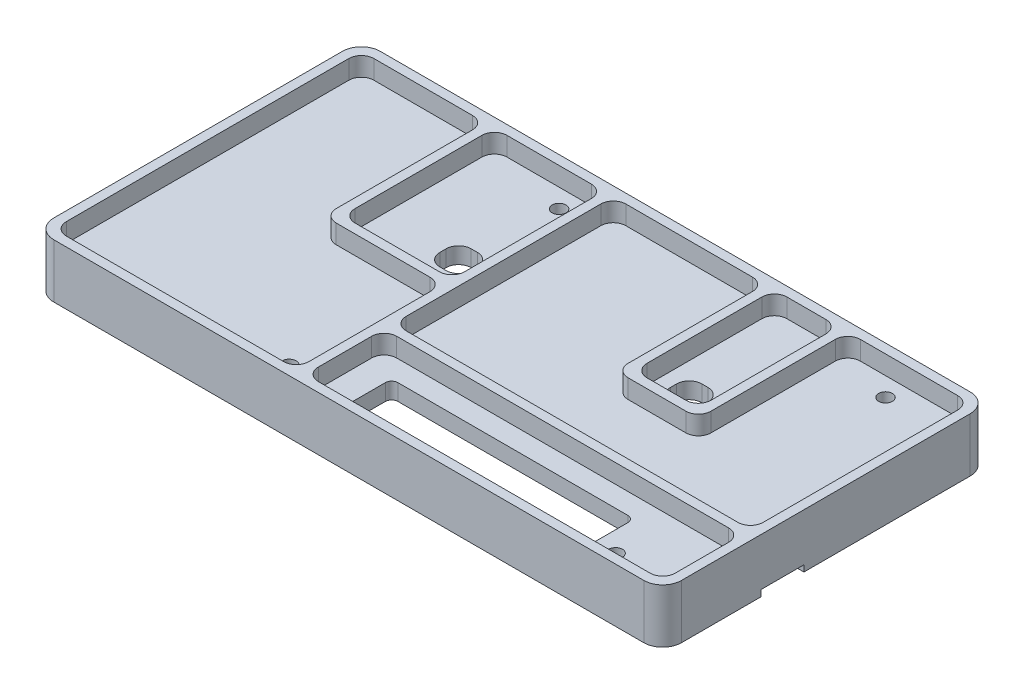
SolidWorks part; units mm, degrees
ref_plane "Front Plane" through (0, 0, 0) normal (0, 0, 1) x (1, 0, 0)
ref_plane "Top Plane" through (0, 0, 0) normal (0, 1, 0) x (1, 0, 0)
ref_plane "Right Plane" through (0, 0, 0) normal (1, 0, 0) x (0, 0, -1)
other "Configuration Table"
sketch "草图1" plane through (0, 0, 0) normal (0, 1, 0) x (1, 0, 0)
  line L1 (-48.8285, 31.982) -> (51.1715, 31.982)
  line L2 (-48.8285, 31.982) -> (-48.8285, -20.018)
  line L3 (-48.8285, -20.018) -> (51.1715, -20.018)
  line L4 (51.1715, 31.982) -> (51.1715, -20.018)
  dimension "D1" = 100
  dimension "D2" = 52
extrude "凸台-拉伸1" add sketch "草图1" along normal blind 8.6
sketch "草图2" plane through (0, 0, 0) normal (0, -1, 0) x (1, 0, 0)
  line L0 (51.1715, -31.982) -> (-48.8285, -31.982) construction
  line L1 (49.6715, -30.482) -> (-47.3285, -30.482)
  line L2 (49.6715, -30.482) -> (49.6715, 18.518)
  line L3 (49.6715, 18.518) -> (-47.3285, 18.518)
  line L4 (-47.3285, -30.482) -> (-47.3285, 18.518)
  line L5 (-48.8285, -31.982) -> (-48.8285, 20.018) construction
  line L6 (-48.8285, 20.018) -> (51.1715, 20.018) construction
  line L7 (51.1715, 20.018) -> (51.1715, -31.982) construction
  dimension "D1" = 1.5
  dimension "D2" = 1.5
  dimension "D3" = 1.5
  dimension "D4" = 1.5
extrude "切除-拉伸1" cut sketch "草图2" against normal blind 3
sketch "草图3" plane through (0, 3, 0) normal (0, -1, 0) x (1, 0, 0)
  line L0 (51.1715, -31.982) -> (-48.8285, -31.982) construction
  line L1 (35.9314, 9.319) -> (-2.7006, 9.319)
  line L2 (35.9314, 9.319) -> (35.9314, 16.7184)
  line L3 (35.9314, 16.7184) -> (-2.7006, 16.7184)
  line L4 (-2.7006, 9.319) -> (-2.7006, 16.7184)
  line L5 (-16.3285, -9.982) -> (-11.3285, -9.982)
  line L6 (-16.3285, -9.982) -> (-16.3285, -14.982)
  line L7 (-16.3285, -14.982) -> (-11.3285, -14.982)
  line L8 (-11.3285, -9.982) -> (-11.3285, -14.982)
  line L9 (-48.8285, -31.982) -> (-48.8285, 20.018) construction
  line L10 (48.159, -31.7129) -> (-45.8412, -31.7129) construction
  line L11 (20.6715, -9.7129) -> (25.6715, -9.7129)
  line L12 (20.6715, -9.7129) -> (20.6715, -14.7129)
  line L13 (20.6715, -14.7129) -> (25.6715, -14.7129)
  line L14 (25.6715, -9.7129) -> (25.6715, -14.7129)
  line L15 (51.1715, 20.018) -> (51.1715, -31.982) construction
  line L16 (-48.8285, 20.018) -> (51.1715, 20.018) construction
  circle A0 centre (-12.8285, 15.518) radius 1.1
  circle A1 centre (39.1715, 15.518) radius 1.1
  circle A2 centre (39.1715, -27.482) radius 1.1
  circle A3 centre (-12.8285, -27.482) radius 1.1
  dimension "D9" = 4.5
  dimension "D1" = 5
  dimension "D2" = 5
  dimension "D3" = 17
  dimension "D4" = 32.5
  dimension "D5" = 5
  dimension "D6" = 5
  dimension "D7" = 17
  dimension "D8" = 25.5
  dimension "D10" = 36
  dimension "D11" = 4.5
  dimension "D12" = 12
  dimension "D13" = 12
  dimension "D14" = 4.5
  dimension "D15" = 4.5
  dimension "D16" = 36
extrude "切除-拉伸2" cut sketch "草图3" against normal through all
sketch "草图8" plane through (0, 3, 0) normal (0, -1, 0) x (1, 0, 0)
  circle A0 centre (39.1715, -27.482) radius 2
  circle A1 centre (-12.8285, -27.482) radius 2
  circle A2 centre (-12.8285, 15.518) radius 2
  circle A3 centre (39.1715, 15.518) radius 2
fillet "圆角1" radius 2 8 edges at (25.6715, 5.8, -14.7129) (25.6715, 5.8, -9.7129) (20.6715, 5.8, -9.7129) (20.6715, 5.8, -14.7129) (-16.3285, 5.8, -14.982) (-11.3285, 5.8, -14.982) (-11.3285, 5.8, -9.982) (-16.3285, 5.8, -9.982)
sketch "草图4" plane through (0, 0, 0) normal (0, -1, 0) x (1, 0, 0)
  line L0 (51.1715, 20.018) -> (51.1715, -31.982) construction
  line L1 (51.1715, -2.482) -> (49.6715, -2.482)
  line L2 (51.1715, -2.482) -> (51.1715, 4.318)
  line L3 (51.1715, 4.318) -> (49.6715, 4.318)
  line L4 (49.6715, -2.482) -> (49.6715, 4.318)
  line L5 (49.6715, -30.482) -> (49.6715, 18.518) construction
  line L6 (51.1715, -31.982) -> (-48.8285, -31.982) construction
  dimension "D1" = 29.5
  dimension "D2" = 36.3
extrude "切除-拉伸3" cut sketch "草图4" against normal blind 1
sketch "草图5" plane through (0, 8.6, 0) normal (0, 1, 0) x (1, 0, 0)
  line L0 (51.1715, -20.018) -> (51.1715, 31.982) construction
  line L1 (-47.3285, 30.482) -> (49.6715, 30.482)
  line L2 (-47.3285, 30.482) -> (-47.3285, -18.518)
  line L3 (-47.3285, -18.518) -> (49.6715, -18.518)
  line L4 (49.6715, 30.482) -> (49.6715, -18.518)
  line L5 (-48.8285, -20.018) -> (51.1715, -20.018) construction
  line L6 (-48.8285, 31.982) -> (-48.8285, -20.018) construction
  line L7 (51.1715, 31.982) -> (-48.8285, 31.982) construction
  dimension "D1" = 1.5
  dimension "D2" = 1.5
  dimension "D3" = 1.5
  dimension "D4" = 1.5
extrude "切除-拉伸4" cut sketch "草图5" against normal blind 3
sketch "草图7" plane through (0, 5.6, 0) normal (0, 1, 0) x (1, 0, 0)
  line L0 (-8.6885, -18.518) -> (-8.6885, 4.782)
  line L1 (-47.3285, -18.518) -> (49.6715, -18.518) construction
  line L2 (-8.6885, 4.782) -> (-27.6285, 4.782)
  line L3 (-27.6285, 4.782) -> (-27.6285, 30.482)
  line L4 (49.6715, 30.482) -> (-47.3285, 30.482) construction
  line L5 (-27.6285, 30.482) -> (-26.1285, 30.482)
  line L6 (-26.1285, 30.482) -> (-26.1285, 6.282)
  line L7 (-26.1285, 6.282) -> (-8.6885, 6.282)
  line L8 (-8.6885, 6.282) -> (-8.6885, 30.482)
  line L9 (-8.6885, 30.482) -> (-7.1885, 30.482)
  line L10 (-7.1885, 30.482) -> (-7.1885, -4.518)
  line L11 (-7.1885, -4.518) -> (49.6715, -4.518)
  line L12 (49.6715, -18.518) -> (49.6715, 30.482) construction
  line L13 (49.6715, -4.518) -> (49.6715, -6.018)
  line L14 (49.6715, -6.018) -> (-7.1885, -6.018)
  line L15 (-7.1885, -6.018) -> (-7.1885, -18.518)
  line L16 (-7.1885, -18.518) -> (-8.6885, -18.518)
  line L17 (-48.8285, -20.018) -> (51.1715, -20.018) construction
  line L18 (51.1715, -20.018) -> (51.1715, 31.982) construction
  line L19 (51.1715, 31.982) -> (-48.8285, 31.982) construction
  line L20 (16.9715, 30.482) -> (16.9715, 6.682)
  line L21 (16.9715, 6.682) -> (30.1715, 6.682)
  line L22 (30.1715, 6.682) -> (30.1715, 30.482)
  line L23 (30.1715, 30.482) -> (28.6715, 30.482)
  line L24 (28.6715, 30.482) -> (28.6715, 8.182)
  line L25 (28.6715, 8.182) -> (18.4715, 8.182)
  line L26 (18.4715, 8.182) -> (18.4715, 30.482)
  line L27 (18.4715, 30.482) -> (16.9715, 30.482)
  dimension "D1" = 14
  dimension "D2" = 1.5
  dimension "D3" = 58.36
  dimension "D4" = 1.5
  dimension "D5" = 78.8
  dimension "D6" = 27.2
  dimension "D7" = 1.5
  dimension "D8" = 1.5
  dimension "D9" = 21
  dimension "D10" = 25.3
  dimension "D11" = 34.2
  dimension "D12" = 1.5
  dimension "D13" = 1.5
  dimension "D14" = 1.5
extrude "凸台-拉伸2" add sketch "草图7" along normal through all
fillet "圆角2" radius 3 4 edges at (51.1715, 4.3, 20.018) (51.1715, 4.3, -31.982) (-48.8285, 4.3, -31.982) (-48.8285, 4.3, 20.018)
fillet "圆角3" radius 2 30 edges at (-47.3285, 7.1, 18.518) (-47.3285, 7.1, -30.482) (49.6715, 7.1, -30.482) (49.6715, 7.1, 18.518) (49.6715, 1.5, -30.482) (49.6715, 1.5, 18.518) (-47.3285, 1.5, 18.518) (-47.3285, 1.5, -30.482) (-27.6285, 7.1, -4.782) (-27.6285, 7.1, -30.482) (-26.1285, 7.1, -30.482) (-26.1285, 7.1, -6.282) (-8.6885, 7.1, 18.518) (-8.6885, 7.1, -4.782) (-8.6885, 7.1, -6.282) (-8.6885, 7.1, -30.482) (-7.1885, 7.1, -30.482) (18.4715, 7.1, -8.182) (28.6715, 7.1, -8.182) (18.4715, 7.1, -30.482) (28.6715, 7.1, -30.482) (16.9715, 7.1, -30.482) (16.9715, 7.1, -6.682) (30.1715, 7.1, -6.682) (30.1715, 7.1, -30.482) (49.6715, 7.1, 4.518) (-7.1885, 7.1, 4.518) (-7.1885, 7.1, 6.018) (-7.1885, 7.1, 18.518) (49.6715, 7.1, 6.018)
fillet "圆角5" radius 1 4 edges at (35.9314, 4.3, 16.7184) (35.9314, 4.3, 9.319) (-2.7006, 4.3, 9.319) (-2.7006, 4.3, 16.7184)
